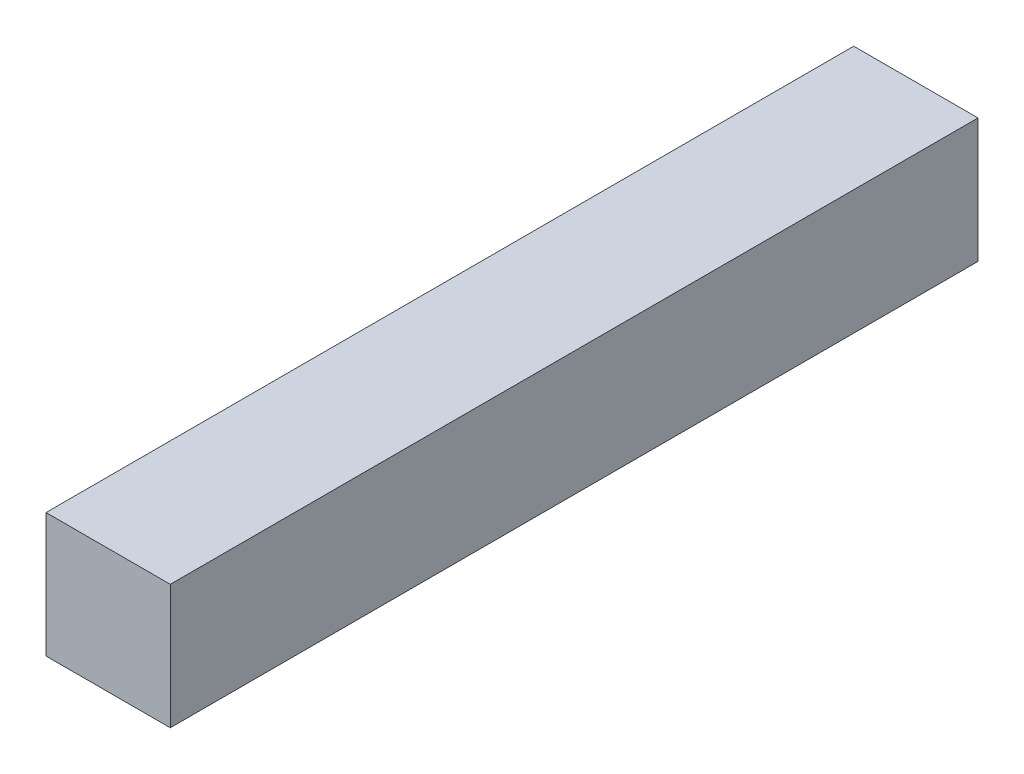
SolidWorks part; units mm, degrees
ref_plane "Front Plane" through (0, 0, 0) normal (0, 0, 1) x (1, 0, 0)
ref_plane "Top Plane" through (0, 0, 0) normal (0, 1, 0) x (1, 0, 0)
ref_plane "Right Plane" through (0, 0, 0) normal (1, 0, 0) x (0, 0, -1)
sketch "Sketch1" plane through (0, 0, 0) normal (0, 0, 1) x (1, 0, 0)
  line L1 (-9.525, -9.525) -> (9.525, -9.525)
  line L2 (-9.525, -9.525) -> (-9.525, 9.525)
  line L3 (-9.525, 9.525) -> (9.525, 9.525)
  line L4 (9.525, -9.525) -> (9.525, 9.525)
  line L5 (-9.525, -9.525) -> (9.525, 9.525) construction
  line L6 (-9.525, 9.525) -> (9.525, -9.525) construction
  point P0 (0, 0)
  dimension "D1" = 19.05
  dimension "D2" = 19.05
extrude "Boss-Extrude1" add sketch "Sketch1" along normal blind 123.825 contours L3 L4 L1 L2
